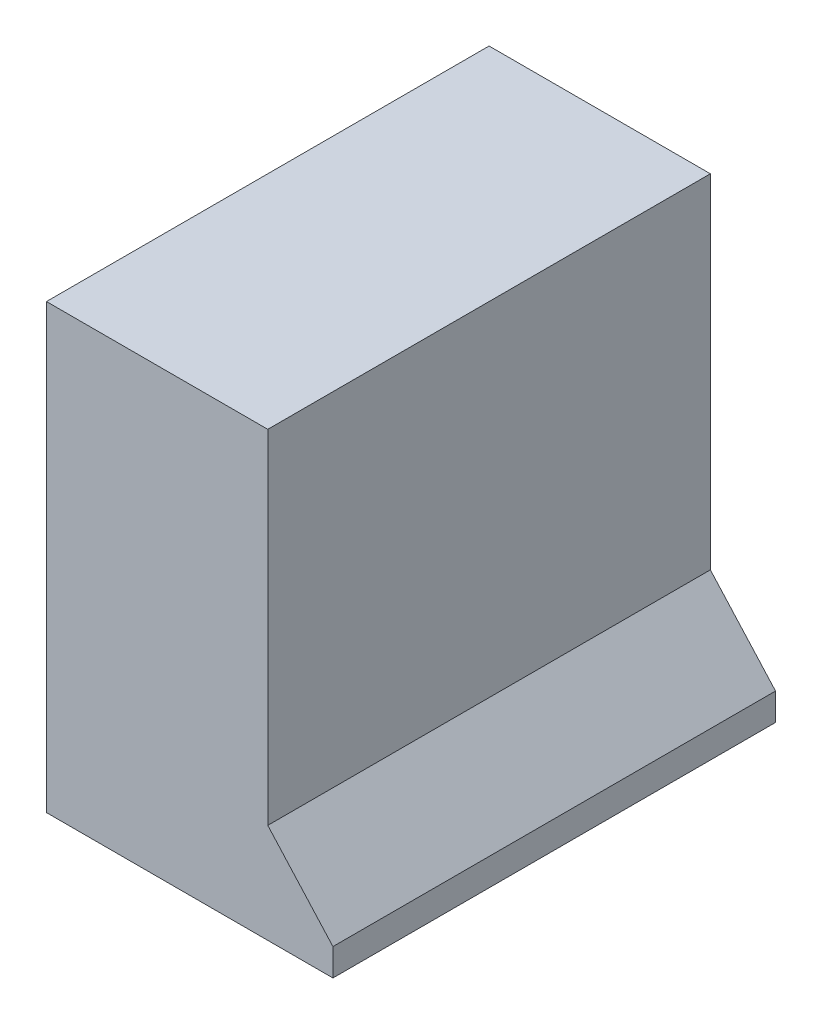
SolidWorks part; units mm, degrees
ref_plane "Plan de face" through (0, 0, 0) normal (0, 0, 1) x (1, 0, 0)
ref_plane "Plan de dessus" through (0, 0, 0) normal (0, 1, 0) x (1, 0, 0)
ref_plane "Plan de droite" through (0, 0, 0) normal (1, 0, 0) x (0, 0, -1)
sketch "Esquisse1" plane through (0, 0, 0) normal (0, 0, 1) x (1, 0, 0)
  line L0 (3574.5151, 20490.8859) -> (3574.5151, -19147.588) construction
  line L1 (-9369.6596, 4200.8203) -> (630.3404, 4200.8203)
  line L2 (-9369.6596, 4200.8203) -> (-9369.6596, -15799.1797)
  line L3 (-9369.6596, -15799.1797) -> (3574.5151, -15799.1797)
  line L4 (3574.5151, -15799.1797) -> (3574.5151, -14569.017)
  line L5 (3574.5151, -14569.017) -> (630.3404, -11299.1797)
  line L6 (630.3404, -11299.1797) -> (630.3404, 4200.8203)
  line L7 (630.3404, -11299.1797) -> (12365.8679, 4892.1397) construction
  dimension "D1" = 4400
  dimension "D2" = 42
  dimension "D3" = 10000
  dimension "D4" = 20000
  dimension "D5" = 15500
extrude "Boss.-Extru.1" add sketch "Esquisse1" along normal blind 20000
